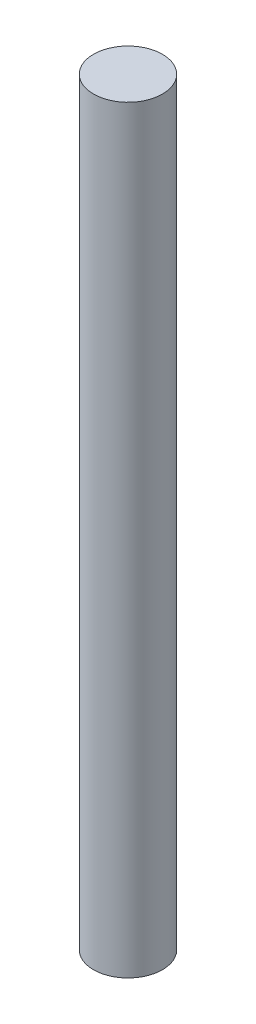
SolidWorks part; units mm, degrees
ref_plane "Front Plane" through (0, 0, 0) normal (0, 0, 1) x (1, 0, 0)
ref_plane "Top Plane" through (0, 0, 0) normal (0, 1, 0) x (1, 0, 0)
ref_plane "Right Plane" through (0, 0, 0) normal (1, 0, 0) x (0, 0, -1)
sketch "Sketch1" plane through (0, 0, 0) normal (0, 1, 0) x (1, 0, 0)
  circle A0 centre (0, 0) radius 1
  dimension "D1" = 2
extrude "Boss-Extrude1" add sketch "Sketch1" along normal blind 22
